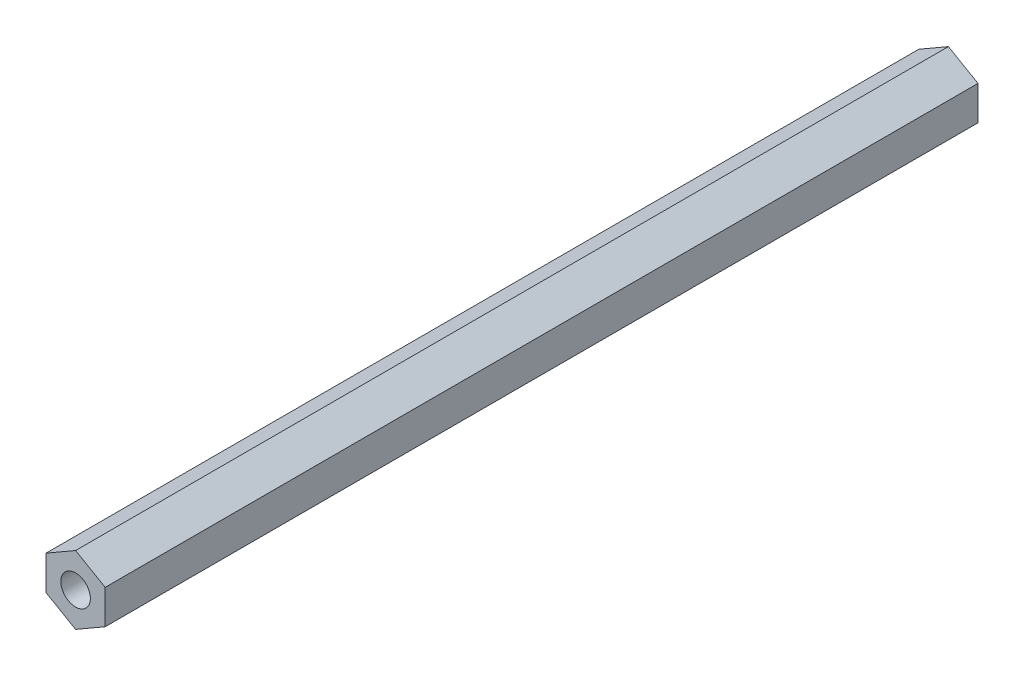
SolidWorks part; units mm, degrees
ref_plane "Front Plane" through (0, 0, 0) normal (0, 0, 1) x (1, 0, 0)
ref_plane "Top Plane" through (0, 0, 0) normal (0, 1, 0) x (1, 0, 0)
ref_plane "Right Plane" through (0, 0, 0) normal (1, 0, 0) x (0, 0, -1)
sketch "Sketch1" plane through (0, 0, 0) normal (0, 0, 1) x (1, 0, 0)
  line L1 (0, 7.3323) -> (-6.35, 3.6662)
  line L2 (-6.35, 3.6662) -> (-6.35, -3.6662)
  line L3 (-6.35, -3.6662) -> (0, -7.3323)
  line L4 (0, -7.3323) -> (6.35, -3.6662)
  line L5 (6.35, -3.6662) -> (6.35, 3.6662)
  line L6 (6.35, 3.6662) -> (0, 7.3323)
  circle A0 centre (0, 0) radius 6.35 construction
  circle A1 centre (0, 0) radius 3.175
  dimension "D2" = 6.35
  dimension "D1" = 12.7
extrude "Boss-Extrude1" add sketch "Sketch1" along normal blind 187.325
